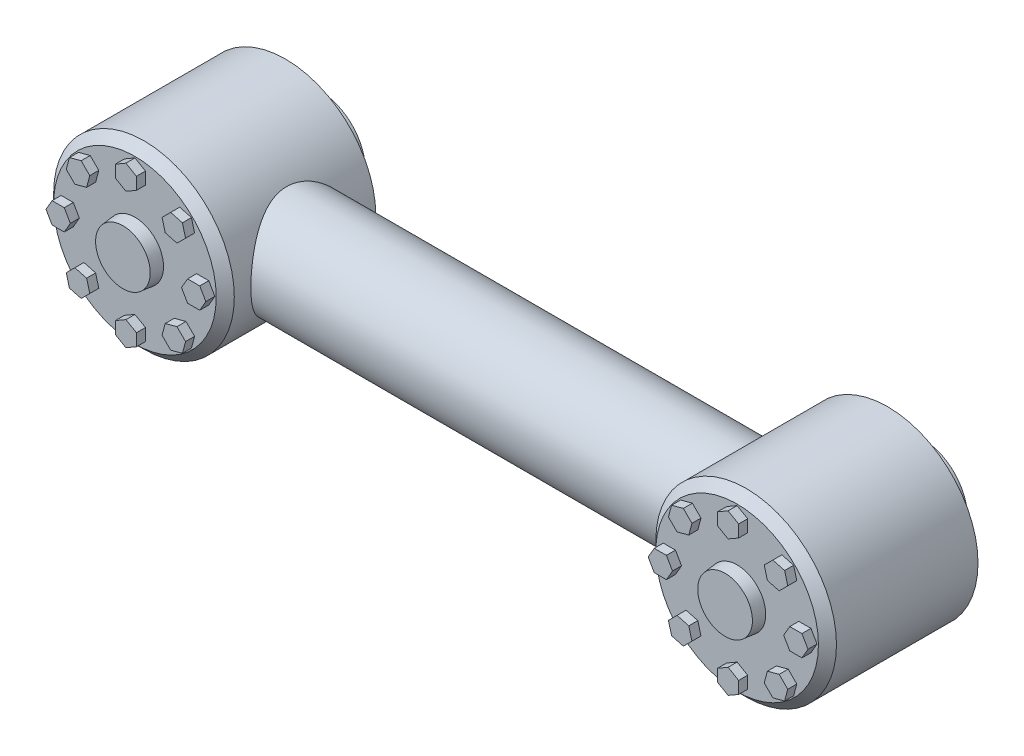
SolidWorks part; units mm, degrees
ref_plane "Front Plane" through (0, 0, 0) normal (0, 0, 1) x (1, 0, 0)
ref_plane "Top Plane" through (0, 0, 0) normal (0, 1, 0) x (1, 0, 0)
ref_plane "Right Plane" through (0, 0, 0) normal (1, 0, 0) x (0, 0, -1)
sketch "Sketch1" plane through (0, 0, 0) normal (0, 0, 1) x (1, 0, 0)
  circle A0 centre (0, 0) radius 30
  dimension "D1" = 60
extrude "Boss-Extrude1" add sketch "Sketch1" along normal mid plane 50
sketch "Sketch2" plane through (0, 0, -25) normal (0, 0, -1) x (-1, 0, 0)
  circle A0 centre (0, 0) radius 15
  dimension "D1" = 30
extrude "Boss-Extrude2" add sketch "Sketch2" along normal blind 11.5
sketch "Sketch3" plane through (0, 0, 25) normal (0, 0, 1) x (1, 0, 0)
  line L0 (0, 0) -> (0, 30) construction
  line L1 (19.8136, 14.8639) -> (18.7676, 18.7676)
  line L2 (0, 18.4585) -> (3.5, 20.4793)
  line L3 (3.5, 20.4793) -> (3.5, 24.5207)
  line L4 (3.5, 24.5207) -> (0, 26.5415)
  line L5 (0, 26.5415) -> (-3.5, 24.5207)
  line L6 (-3.5, 24.5207) -> (-3.5, 20.4793)
  line L7 (-3.5, 20.4793) -> (0, 18.4585)
  line L8 (18.7676, 18.7676) -> (14.8639, 19.8136)
  line L9 (14.8639, 19.8136) -> (12.0062, 16.9559)
  line L10 (12.0062, 16.9559) -> (13.0522, 13.0522)
  line L11 (13.0522, 13.0522) -> (16.9559, 12.0062)
  line L12 (16.9559, 12.0062) -> (19.8136, 14.8639)
  line L13 (24.5207, -3.5) -> (26.5415, 0)
  line L14 (26.5415, 0) -> (24.5207, 3.5)
  line L15 (24.5207, 3.5) -> (20.4793, 3.5)
  line L16 (20.4793, 3.5) -> (18.4585, 0)
  line L17 (18.4585, 0) -> (20.4793, -3.5)
  line L18 (20.4793, -3.5) -> (24.5207, -3.5)
  line L19 (14.8639, -19.8136) -> (18.7676, -18.7676)
  line L20 (18.7676, -18.7676) -> (19.8136, -14.8639)
  line L21 (19.8136, -14.8639) -> (16.9559, -12.0062)
  line L22 (16.9559, -12.0062) -> (13.0522, -13.0522)
  line L23 (13.0522, -13.0522) -> (12.0062, -16.9559)
  line L24 (12.0062, -16.9559) -> (14.8639, -19.8136)
  line L25 (-3.5, -24.5207) -> (0, -26.5415)
  line L26 (0, -26.5415) -> (3.5, -24.5207)
  line L27 (3.5, -24.5207) -> (3.5, -20.4793)
  line L28 (3.5, -20.4793) -> (0, -18.4585)
  line L29 (0, -18.4585) -> (-3.5, -20.4793)
  line L30 (-3.5, -20.4793) -> (-3.5, -24.5207)
  line L31 (-19.8136, -14.8639) -> (-18.7676, -18.7676)
  line L32 (-18.7676, -18.7676) -> (-14.8639, -19.8136)
  line L33 (-14.8639, -19.8136) -> (-12.0062, -16.9559)
  line L34 (-12.0062, -16.9559) -> (-13.0522, -13.0522)
  line L35 (-13.0522, -13.0522) -> (-16.9559, -12.0062)
  line L36 (-16.9559, -12.0062) -> (-19.8136, -14.8639)
  line L37 (-24.5207, 3.5) -> (-26.5415, 0)
  line L38 (-26.5415, 0) -> (-24.5207, -3.5)
  line L39 (-24.5207, -3.5) -> (-20.4793, -3.5)
  line L40 (-20.4793, -3.5) -> (-18.4585, 0)
  line L41 (-18.4585, 0) -> (-20.4793, 3.5)
  line L42 (-20.4793, 3.5) -> (-24.5207, 3.5)
  line L43 (-14.8639, 19.8136) -> (-18.7676, 18.7676)
  line L44 (-18.7676, 18.7676) -> (-19.8136, 14.8639)
  line L45 (-19.8136, 14.8639) -> (-16.9559, 12.0062)
  line L46 (-16.9559, 12.0062) -> (-13.0522, 13.0522)
  line L47 (-13.0522, 13.0522) -> (-12.0062, 16.9559)
  line L48 (-12.0062, 16.9559) -> (-14.8639, 19.8136)
  circle A0 centre (0, 0) radius 30 construction
  circle A1 centre (0, 0) radius 22.5 construction
  circle A2 centre (0, 22.5) radius 3.5 construction
  point P59 (0, 0)
  dimension "D1" = 45
  dimension "D2" = 7
  dimension "D3" = 8
extrude "Boss-Extrude3" add sketch "Sketch3" along normal blind 3
chamfer "Chamfer1" distance 3 angle 45 1 edges at (30, 0, 25)
sketch "Sketch4" plane through (0, 0, 0) normal (1, 0, 0) x (0, 0, -1)
  line L0 (25, 0) -> (-25, 0) construction
  circle A0 centre (1, 0) radius 17.5
  point P6 (0, 0)
  dimension "D1" = 35
  dimension "D2" = 1
extrude "Boss-Extrude4" add sketch "Sketch4" along normal blind 200
ref_plane "Plane1" through (100, 0, 0) normal (1, 0, 0) x (0, 0, -1)
mirror "Mirror1" about plane through (100, 0, 0) normal (1, 0, 0) of "Chamfer1", "Boss-Extrude1"
mirror "Mirror2" about plane through (100, 0, 0) normal (1, 0, 0) of "Boss-Extrude2", "Boss-Extrude3"
sketch "Sketch5" plane through (0, 0, 25) normal (0, 0, 1) x (1, 0, 0)
  circle A0 centre (0, 0) radius 9.5
  dimension "D1" = 19
extrude "Boss-Extrude5" add sketch "Sketch5" along normal blind 4 draft 6
mirror "Mirror3" about plane through (100, 0, 0) normal (1, 0, 0) of "Boss-Extrude5"
